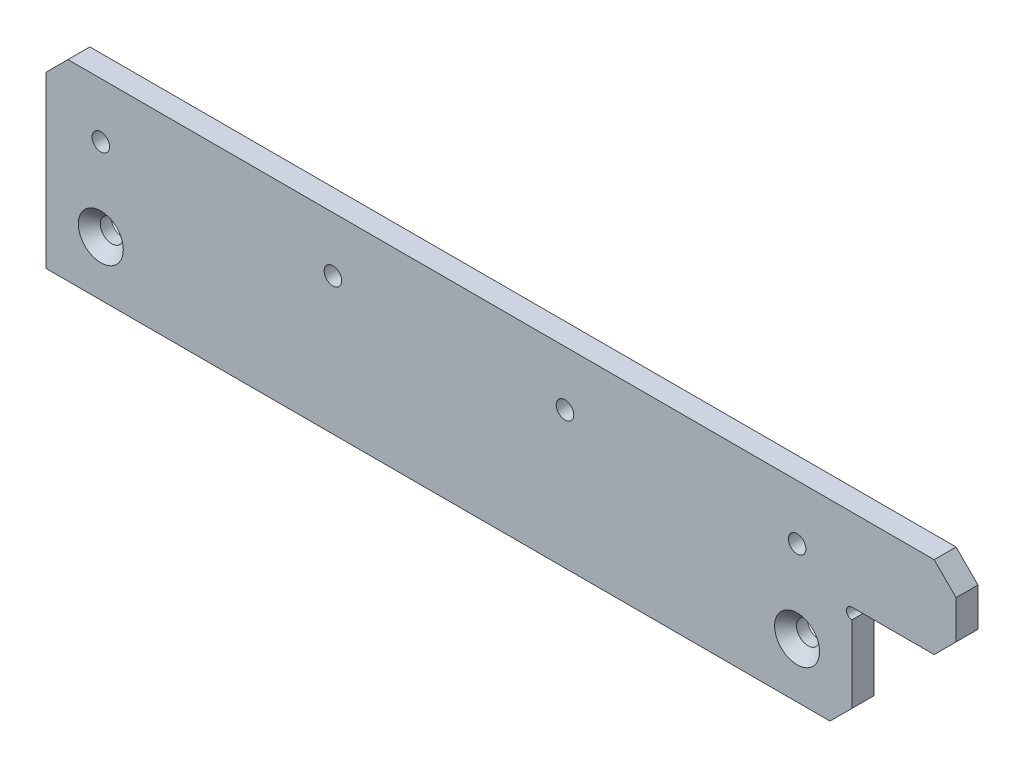
SolidWorks part; units mm, degrees
ref_plane "前视基准面" through (0, 0, 0) normal (0, 0, 1) x (1, 0, 0)
ref_plane "上视基准面" through (0, 0, 0) normal (0, 1, 0) x (1, 0, 0)
ref_plane "右视基准面" through (0, 0, 0) normal (1, 0, 0) x (0, 0, -1)
sketch "草图1" plane through (0, 0, 0) normal (0, 0, 1) x (1, 0, 0)
  line L1 (73.5, -17.5) -> (-73.5, -17.5)
  line L2 (73.5, -17.5) -> (73.5, 17.5)
  line L3 (73.5, 17.5) -> (-73.5, 17.5)
  line L4 (-73.5, -17.5) -> (-73.5, 17.5)
  line L5 (73.5, -17.5) -> (-73.5, 17.5) construction
  line L6 (73.5, 17.5) -> (-73.5, -17.5) construction
  point P0 (0, 0)
  dimension "D1" = 35
  dimension "D2" = 147
extrude "凸台-拉伸1" add sketch "草图1" along normal mid plane 4
sketch "草图2" plane through (0, 0, 2) normal (0, 0, 1) x (1, 0, 0)
  line L1 (73.5, 17.5) -> (92.5, 17.5)
  line L2 (73.5, 17.5) -> (73.5, 2.5)
  line L3 (73.5, 2.5) -> (92.5, 2.5)
  line L4 (92.5, 17.5) -> (92.5, 2.5)
  dimension "D1" = 15
  dimension "D2" = 19
extrude "凸台-拉伸2" add sketch "草图2" against normal blind 4
sketch "草图3" plane through (0, 0, 2) normal (0, 0, 1) x (1, 0, 0)
  line L0 (-63.5, -7.5) -> (63.5, -7.5) construction
  line L1 (-73.5, 17.5) -> (-73.5, -17.5) construction
  line L2 (-73.5, -17.5) -> (73.5, -17.5) construction
  line L3 (73.5, -17.5) -> (73.5, 2.5) construction
  circle A0 centre (-63.5, -7.5) radius 2.1
  circle A1 centre (63.5, -7.5) radius 2.1
  dimension "D1" = 4.2
  dimension "D2" = 10
  dimension "D4" = 10
  dimension "D3" = 10
extrude "切除-拉伸1" cut sketch "草图3" against normal through all
chamfer "倒角1" distance 4 angle 45 4 edges at (92.5, 2.5, 0) (73.5, -17.5, 0) (-73.5, 17.5, 0) (92.5, 17.5, 0)
sketch "草图4" plane through (0, 0, 2) normal (0, 0, 1) x (1, 0, 0)
  line L0 (73.5, -13.5) -> (73.5, 2.5) construction
  circle A0 centre (73.5, 1.5) radius 1
  dimension "D1" = 2
extrude "切除-拉伸2" cut sketch "草图4" against normal through all
sketch "草图5" plane through (0, 0, 2) normal (0, 0, 1) x (1, 0, 0)
  line L0 (-63.5, 7.5) -> (-21.1667, 7.5) construction
  line L1 (-21.1667, 7.5) -> (21.1667, 7.5) construction
  line L2 (21.1667, 7.5) -> (63.5, 7.5) construction
  line L3 (-73.5, 13.5) -> (-73.5, -17.5) construction
  line L4 (-73.5, -17.5) -> (69.5, -17.5) construction
  circle A0 centre (-63.5, 7.5) radius 1.6
  circle A1 centre (-21.1667, 7.5) radius 1.6
  circle A2 centre (21.1667, 7.5) radius 1.6
  circle A3 centre (63.5, 7.5) radius 1.6
  point P8 (0, 7.5)
  dimension "D1" = 3.2
  dimension "D2" = 10
  dimension "D3" = 25
extrude "切除-拉伸3" cut sketch "草图5" against normal through all
chamfer "倒角2" distance 2 angle 45 2 edges at (65.6, -7.5, 2) (-61.4, -7.5, 2)
